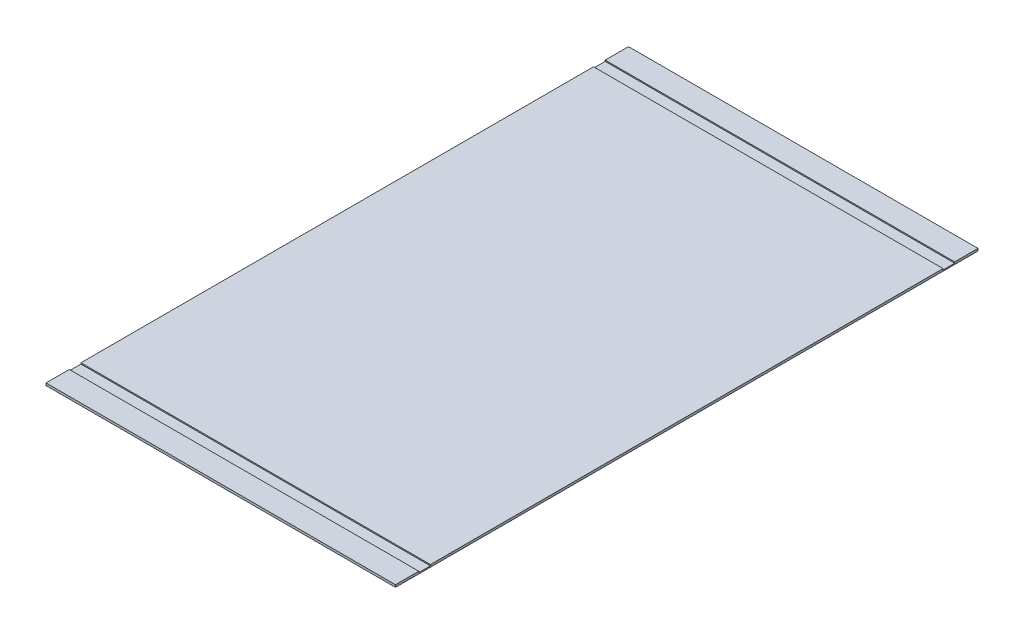
SolidWorks part; units mm, degrees
ref_plane "Front Plane" through (0, 0, 0) normal (0, 0, 1) x (1, 0, 0)
ref_plane "Top Plane" through (0, 0, 0) normal (0, 1, 0) x (1, 0, 0)
ref_plane "Right Plane" through (0, 0, 0) normal (1, 0, 0) x (0, 0, -1)
sketch "Sketch1" plane through (0, 0, 0) normal (0, 1, 0) x (1, 0, 0)
  line L1 (0, 0) -> (-381, 0)
  line L2 (0, 0) -> (0, 635)
  line L3 (0, 635) -> (-381, 635)
  line L4 (-381, 0) -> (-381, 635)
  dimension "D1" = 381
  dimension "D2" = 635
extrude "Boss-Extrude1" add sketch "Sketch1" along normal blind 2.54
sketch "Sketch2" plane through (0, 2.54, 0) normal (0, 1, 0) x (1, 0, 0)
  line L0 (-381, 596.9) -> (0, 596.9)
  line L1 (-381, 635) -> (-381, 0) construction
  line L2 (0, 0) -> (0, 635) construction
  line L3 (0, 596.9) -> (0, 609.6)
  line L4 (0, 609.6) -> (-381, 609.6)
  line L5 (-381, 609.6) -> (-381, 596.9)
  line L6 (0, 635) -> (-381, 635) construction
  line L7 (0, 25.4) -> (-381, 25.4)
  line L8 (-381, 25.4) -> (-381, 38.1)
  line L9 (-381, 38.1) -> (0, 38.1)
  line L10 (0, 38.1) -> (0, 25.4)
  line L11 (-381, 0) -> (0, 0) construction
  dimension "D1" = 12.7
  dimension "D2" = 25.4
  dimension "D3" = 12.7
  dimension "D4" = 25.4
extrude "Cut-Extrude1" cut sketch "Sketch2" against normal blind 1.27
